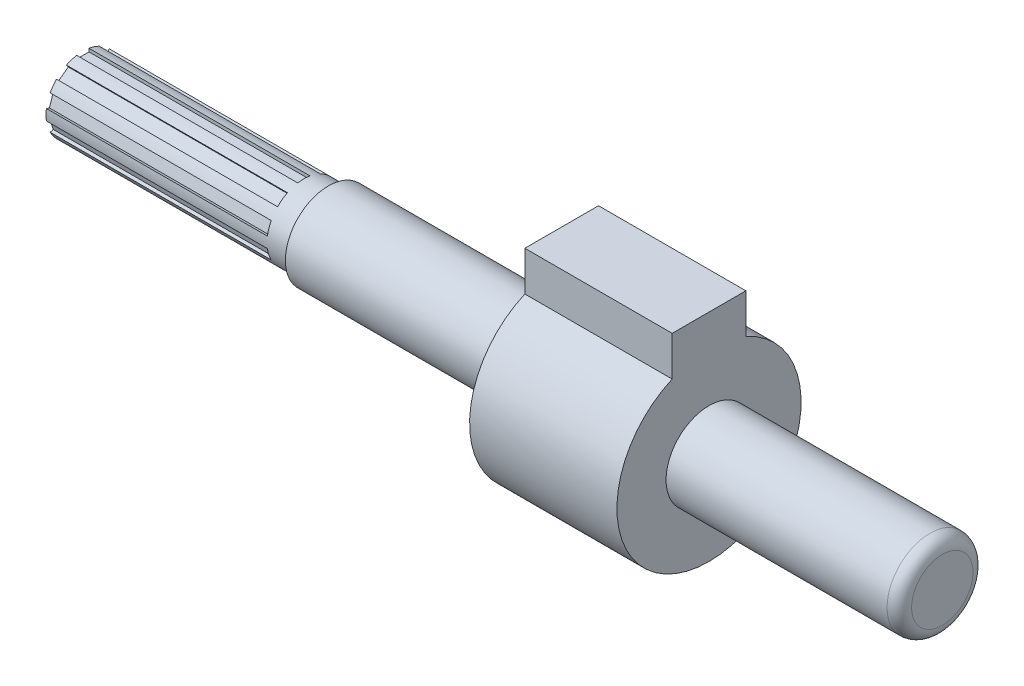
SolidWorks part; units mm, degrees
ref_plane "Ön Düzlem" through (0, 0, 0) normal (0, 0, 1) x (1, 0, 0)
ref_plane "Üst Düzlem" through (0, 0, 0) normal (0, 1, 0) x (1, 0, 0)
ref_plane "Sağ Düzlem" through (0, 0, 0) normal (1, 0, 0) x (0, 0, -1)
sketch "Çizim1" plane through (0, 0, 0) normal (0, 0, 1) x (1, 0, 0)
  line L0 (0, 0) -> (70, 0)
  line L1 (70, 0) -> (70, 2.5)
  line L2 (69, 3.5) -> (51, 3.5)
  line L3 (51, 3.5) -> (51, 7.5)
  line L4 (51, 7.5) -> (39, 7.5)
  line L5 (39, 7.5) -> (39, 3.5)
  line L6 (39, 3.5) -> (0, 3.5)
  line L7 (0, 3.5) -> (0, 0)
  arc A0 (70, 2.5) -> (69, 3.5) centre (69, 2.5) ccw
  point P11 (70, 3.5)
  dimension "D7" = 1
  dimension "D1" = 12
  dimension "D2" = 19
  dimension "D3" = 39
  dimension "D4" = 3.5
  dimension "D5" = 7.5
  dimension "D6" = 3.5
revolve "Döndür1" add sketch "Çizim1" angle 360 about L0
sketch "Çizim2" plane through (51, 0, 0) normal (1, 0, 0) x (0, 0, -1)
  line L1 (-3, 10.1) -> (3, 10.1)
  line L2 (-3, 10.1) -> (-3, 6.8739)
  line L4 (3, 10.1) -> (3, 6.8739)
  circle A0 centre (0, 0) radius 7.5 construction
  arc A1 (3, 6.8739) -> (-3, 6.8739) centre (0, 0) ccw
  dimension "D1" = 10.1
  dimension "D2" = 6
  dimension "D3" = 3
extrude "Yükseklik-Ekstrüzyon2" add sketch "Çizim2" against normal up to surface (12 mm away) up to face at (39, 0, 3.5)
sketch "Çizim3" plane through (0, 0, 0) normal (-1, 0, 0) x (0, 0, 1)
  line L0 (1.1825, 2.4782) -> (1.9915, 1.8905)
  line L2 (-0.5, 3.4641) -> (-0.5, 2.7)
  line L3 (-0.5, 2.7) -> (0.5, 2.7)
  line L4 (0.5, 3.4641) -> (0.5, 2.7)
  line L5 (1.6316, 3.0964) -> (1.1825, 2.4782)
  line L6 (2.4407, 2.5086) -> (1.9915, 1.8905)
  line L7 (2.4133, 1.3099) -> (2.7224, 0.3588)
  line L8 (3.14, 1.546) -> (2.4133, 1.3099)
  line L9 (3.4491, 0.5949) -> (2.7224, 0.3588)
  line L10 (2.7224, -0.3588) -> (2.4133, -1.3099)
  line L11 (3.4491, -0.5949) -> (2.7224, -0.3588)
  line L12 (3.14, -1.546) -> (2.4133, -1.3099)
  line L13 (1.9915, -1.8905) -> (1.1825, -2.4782)
  line L14 (2.4407, -2.5086) -> (1.9915, -1.8905)
  line L15 (1.6316, -3.0964) -> (1.1825, -2.4782)
  line L16 (0.5, -2.7) -> (-0.5, -2.7)
  line L17 (0.5, -3.4641) -> (0.5, -2.7)
  line L18 (-0.5, -3.4641) -> (-0.5, -2.7)
  line L19 (-1.1825, -2.4782) -> (-1.9915, -1.8905)
  line L20 (-1.6316, -3.0964) -> (-1.1825, -2.4782)
  line L21 (-2.4407, -2.5086) -> (-1.9915, -1.8905)
  line L22 (-2.4133, -1.3099) -> (-2.7224, -0.3588)
  line L23 (-3.14, -1.546) -> (-2.4133, -1.3099)
  line L24 (-3.4491, -0.5949) -> (-2.7224, -0.3588)
  line L25 (-2.7224, 0.3588) -> (-2.4133, 1.3099)
  line L26 (-3.4491, 0.5949) -> (-2.7224, 0.3588)
  line L27 (-3.14, 1.546) -> (-2.4133, 1.3099)
  line L28 (-1.9915, 1.8905) -> (-1.1825, 2.4782)
  line L29 (-2.4407, 2.5086) -> (-1.9915, 1.8905)
  line L30 (-1.6316, 3.0964) -> (-1.1825, 2.4782)
  circle A0 centre (0, 0) radius 3.5 construction
  arc A1 (0.5, 3.4641) -> (-0.5, 3.4641) centre (0, 0) ccw
  arc A2 (2.4407, 2.5086) -> (1.6316, 3.0964) centre (0, 0) ccw
  arc A3 (3.4491, 0.5949) -> (3.14, 1.546) centre (0, 0) ccw
  arc A4 (3.14, -1.546) -> (3.4491, -0.5949) centre (0, 0) ccw
  arc A5 (1.6316, -3.0964) -> (2.4407, -2.5086) centre (0, 0) ccw
  arc A6 (-0.5, -3.4641) -> (0.5, -3.4641) centre (0, 0) ccw
  arc A7 (-2.4407, -2.5086) -> (-1.6316, -3.0964) centre (0, 0) ccw
  arc A8 (-3.4491, -0.5949) -> (-3.14, -1.546) centre (0, 0) ccw
  arc A9 (-3.14, 1.546) -> (-3.4491, 0.5949) centre (0, 0) ccw
  arc A10 (-1.6316, 3.0964) -> (-2.4407, 2.5086) centre (0, 0) ccw
  point P44 (0, 0)
  dimension "D1" = 1
  dimension "D2" = 0.5
  dimension "D3" = 2.7
  dimension "D4" = 10
extrude "Kes-Ekstrüzyon1" cut sketch "Çizim3" against normal blind 18
sketch "Çizim4" plane through (0, 0, 0) normal (-1, 0, 0) x (0, 0, 1)
  circle A0 centre (0, 0) radius 3
  circle A1 centre (0, 0) radius 3.5
  dimension "D1" = 6
  dimension "D2" = 7
extrude "Kes-Ekstrüzyon2" cut sketch "Çizim4" against normal blind 20
